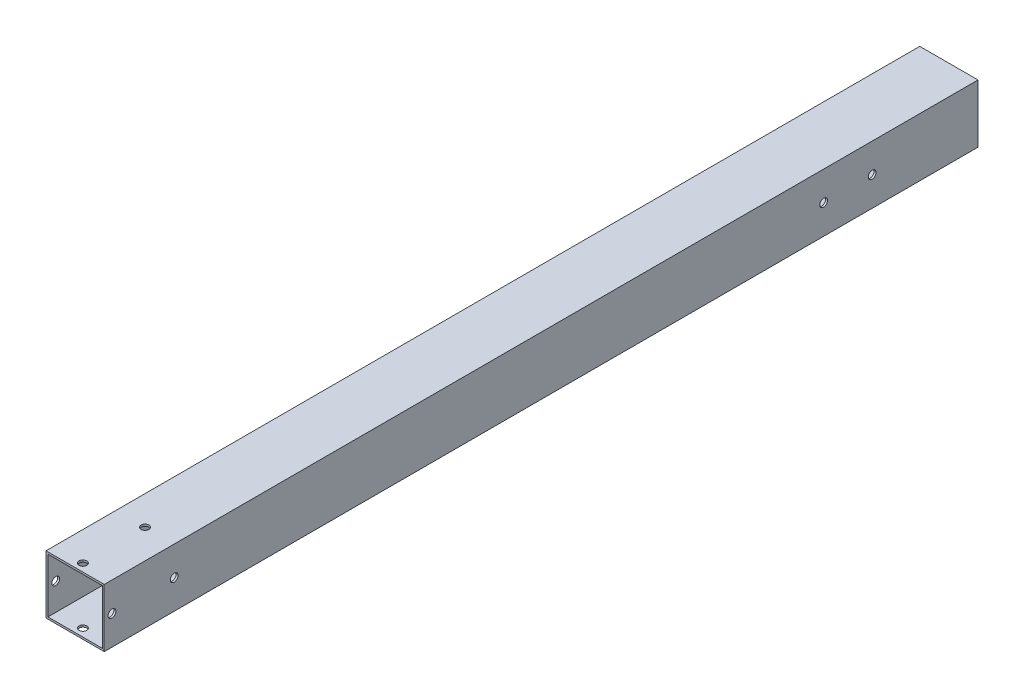
SolidWorks part; units mm, degrees
material "6063-T5"
ref_plane "前视基准面" through (0, 0, 0) normal (0, 0, 1) x (1, 0, 0)
ref_plane "上视基准面" through (0, 0, 0) normal (0, 1, 0) x (1, 0, 0)
ref_plane "右视基准面" through (0, 0, 0) normal (1, 0, 0) x (0, 0, -1)
sketch "草图1" plane through (0, 0, 0) normal (0, 0, 1) x (1, 0, 0)
  line L0 (-14, -14) -> (-14, 14)
  line L1 (-15, -15) -> (15, -15)
  line L2 (-15, -15) -> (-15, 15)
  line L3 (-15, 15) -> (15, 15)
  line L4 (15, -15) -> (15, 15)
  line L5 (0, 15) -> (0, -15) construction
  line L6 (-15, 0) -> (15, 0) construction
  line L7 (-14, 14) -> (14, 14)
  line L8 (14, -14) -> (14, 14)
  line L9 (-14, -14) -> (14, -14)
  point P0 (0, 0)
  dimension "D1" = 30
  dimension "D2" = 30
  dimension "D3" = 1
extrude "凸台-拉伸1" add sketch "草图1" along normal mid plane 450
sketch "草图2" plane through (15, 0, 0) normal (1, 0, 0) x (0, 0, -1)
  circle A0 centre (145.5, 0) radius 2 construction
  circle A1 centre (170.5, 0) radius 2 construction
  circle A2 centre (145.5, 0) radius 2
  circle A3 centre (170.5, 0) radius 2
extrude "切除-拉伸1" cut sketch "草图2" against normal mid plane 130
sketch "草图4" plane through (0, -15, 0) normal (0, -1, 0) x (1, 0, 0)
  circle A0 centre (0, 189) radius 1.65 construction
  circle A1 centre (0, 221) radius 1.65 construction
  circle A2 centre (0, 189) radius 1.65 construction
  circle A3 centre (0, 221) radius 1.65 construction
  circle A4 centre (0, 221) radius 2
  circle A5 centre (0, 189) radius 2
  dimension "D1" = 4
extrude "切除-拉伸2" cut sketch "草图4" against normal mid plane 90
sketch "草图5" plane through (15, 0, 0) normal (1, 0, 0) x (0, 0, -1)
  line L0 (-191, -15) -> (-187, -15) construction
  line L1 (-223, -15) -> (-219, -15) construction
  line L2 (-191, -15) -> (-187, -15) construction
  line L3 (-223, -15) -> (-219, -15) construction
  line L4 (-221, -15) -> (-221, 0) construction
  line L5 (-221, 0) -> (-225, 0) construction
  line L6 (-225, -15) -> (-225, 15) construction
  line L7 (-221, 0) -> (-189, 0) construction
  line L8 (-189, 0) -> (-189, -15) construction
  circle A0 centre (-221, 0) radius 2
  circle A1 centre (-189, 0) radius 2
  dimension "D1" = 4
extrude "切除-拉伸3" cut sketch "草图5" against normal mid plane 90
